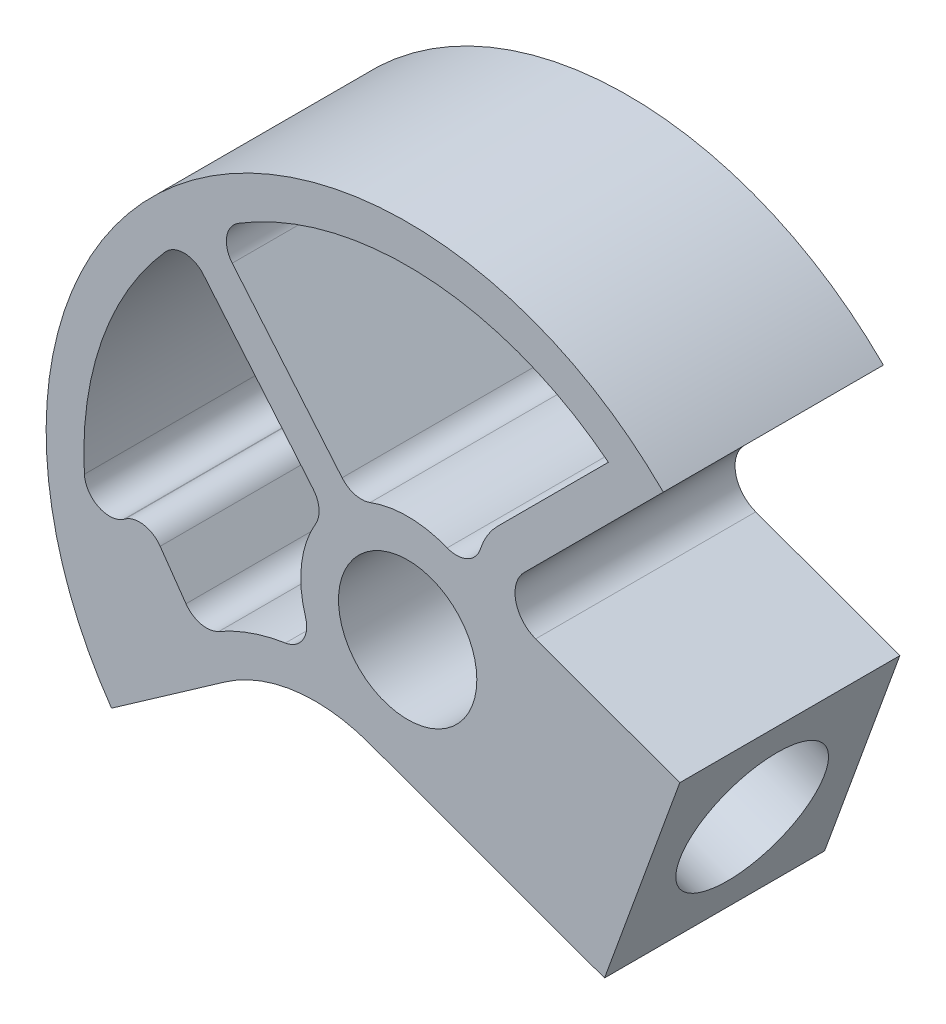
SolidWorks part; units mm, degrees
ref_plane "Front Plane" through (0, 0, 0) normal (0, 0, 1) x (1, 0, 0)
ref_plane "Top Plane" through (0, 0, 0) normal (0, 1, 0) x (1, 0, 0)
ref_plane "Right Plane" through (0, 0, 0) normal (1, 0, 0) x (0, 0, -1)
sketch "Sketch1" plane through (0, 0, 0) normal (0, 0, 1) x (1, 0, 0)
  line L0 (0, 0) -> (-47.1012, -32.9806)
  line L1 (0, 0) -> (0, 57.5) construction
  line L2 (0, 0) -> (40.6586, 40.6586)
  line L3 (-51.0007, -26.5552) -> (0, 9.1558)
  line L4 (0, 10.6066) -> (35.008, 45.6146)
  line L7 (-1.6002, 18.2902) -> (43.2789, 1.9556)
  line L8 (43.2789, 1.9556) -> (31.3082, -30.9337)
  line L9 (31.3082, -30.9337) -> (-6.2795, -17.2528)
  circle A0 centre (0, 0) radius 11
  circle A1 centre (0, 0) radius 57.5
  circle A2 centre (0, 0) radius 18.3601
  circle A3 centre (0, 0) radius 50
  point P21 (12.9826, 12.9826)
  dimension "D1" = 115
  dimension "D3" = 22
  dimension "D4" = 35
  dimension "D2" = 125
  dimension "D6" = 7.5
  dimension "D9" = 40
  dimension "D10" = 45
  dimension "D11" = 7.5
  dimension "D12" = 110
  dimension "D5" = 7.5
extrude "Boss-Extrude1" add sketch "Sketch1" along normal blind 35
fillet "Fillet2" radius 25 1 edges at (-15.0397, -10.5309, 17.5)
fillet "Fillet5" radius 5 1 edges at (12.9826, 12.9826, 17.5)
sketch "Sketch4" plane through (0, 0, 35) normal (0, 0, 1) x (1, 0, 0)
  line L0 (-45.3405, -24.4231) -> (-32.4621, -15.4056)
  line L1 (-4.0787, -11.6688) -> (27.7221, -23.2434)
  line L2 (27.7221, -23.2434) -> (35.5886, -1.6304)
  line L3 (35.5886, -1.6304) -> (18.3055, 4.6601)
  line L4 (14.2896, 22.7749) -> (31.9254, 40.4107)
  line L5 (43.2789, 1.9556) -> (20.3577, 10.2982)
  line L6 (18.5322, 18.5322) -> (40.6586, 40.6586)
  line L7 (-47.1012, -32.9806) -> (-29.0207, -20.3205)
  line L8 (-6.1308, -17.307) -> (31.3082, -30.9337)
  line L9 (31.3082, -30.9337) -> (43.2789, 1.9556)
  line L10 (43.2789, 1.9556) -> (20.3577, 10.2982)
  line L11 (18.5322, 18.5322) -> (40.6586, 40.6586)
  line L12 (-47.1012, -32.9806) -> (-29.0207, -20.3205)
  line L13 (-6.1308, -17.307) -> (31.3082, -30.9337)
  line L14 (31.3082, -30.9337) -> (43.2789, 1.9556)
  line L15 (-35.3455, 37.4559) -> (-9.1008, 6.1787)
  line L16 (-30.7492, 41.3127) -> (-4.5045, 10.0354)
  line L17 (0, 0) -> (-33.1036, 39.4513) construction
  line L18 (-41.2447, -21.5552) -> (-44.1126, -17.4595)
  line L19 (-42.8847, -10.4958) -> (-54.4182, -18.5717)
  line L20 (-37.149, -18.6874) -> (-42.8847, -10.4958)
  line L21 (-44.1126, -17.4595) -> (-52.5407, -23.3608)
  line L22 (-55.8927, -13.5002) -> (-41.6569, -3.5322)
  line L23 (-41.6569, -3.5322) -> (-33.0532, -15.8195)
  arc A0 (31.9254, 40.4107) -> (-45.3405, -24.4231) centre (0, 0) ccw
  arc A1 (-4.0787, -11.6688) -> (-32.4621, -15.4056) centre (-14.6813, -40.7993) ccw
  arc A2 (14.2896, 22.7749) -> (18.3055, 4.6601) centre (22.0678, 14.9967) ccw
  arc A3 (18.5322, 18.5322) -> (20.3577, 10.2982) centre (22.0678, 14.9967) ccw
  arc A4 (40.6586, 40.6586) -> (-47.1012, -32.9806) centre (0, 0) ccw
  arc A5 (-6.1308, -17.307) -> (-29.0207, -20.3205) centre (-14.6813, -40.7993) ccw
  arc A6 (18.5322, 18.5322) -> (20.3577, 10.2982) centre (22.0678, 14.9967) ccw
  arc A7 (40.6586, 40.6586) -> (-47.1012, -32.9806) centre (0, 0) ccw
  arc A8 (-6.1308, -17.307) -> (-29.0207, -20.3205) centre (-14.6813, -40.7993) ccw
  circle A9 centre (0, 0) radius 11 construction
  circle A10 centre (0, 0) radius 11
  circle A11 centre (0, 0) radius 17
  dimension "D3" = 3
  dimension "D4" = 3
  dimension "D6" = 5
  dimension "D7" = 5
  dimension "D8" = 5
  dimension "D9" = 5
  dimension "D10" = 5
  dimension "D11" = 5
  dimension "D1" = 0
  dimension "D2" = 6
  dimension "D5" = 6
extrude "Cut-Extrude2" cut sketch "Sketch4" along direction (0, 0, 1) on the side against the normal up to surface (35 mm away) from surface at 0 contours A11 L15 A0 L0 A1 | A11 A2 L4 A0 L16
fillet "Fillet6" radius 4 9 edges at (-13.8843, -9.8096, 17.5) (-13.054, 10.89, 17.5) (-35.3455, 37.4559, 17.5) (-30.7492, 41.3127, 17.5) (-8.4578, 14.7467, 17.5) (11.3124, 12.6898, 17.5) (-50.5649, -9.7696, 17.5) (-33.0532, -15.8195, 17.5) (-41.6569, -3.5322, 17.5)
sketch "Sketch2" plane through (37.5877, -13.6808, 0) normal (0.9397, -0.342, 0) x (0, 0, -1)
  line L0 (-35, 16.6399) -> (0, -18.3601) construction
  line L7 (0, -18.3601) -> (0, 16.6399)
  line L8 (0, 16.6399) -> (-35, 16.6399)
  line L9 (-35, 16.6399) -> (-35, -18.3601)
  line L10 (-35, -18.3601) -> (0, -18.3601)
  line L11 (0, -18.3601) -> (0, 16.6399)
  line L12 (0, 16.6399) -> (-35, 16.6399)
  line L13 (-35, 16.6399) -> (-35, -18.3601)
  line L14 (-35, -18.3601) -> (0, -18.3601)
  circle A0 centre (-17.5, -0.8601) radius 11.5
  dimension "D1" = 23
  dimension "D2" = 0
extrude "Cut-Extrude1" cut sketch "Sketch2" against normal blind 20 contours A0 L0 | L0 A0
